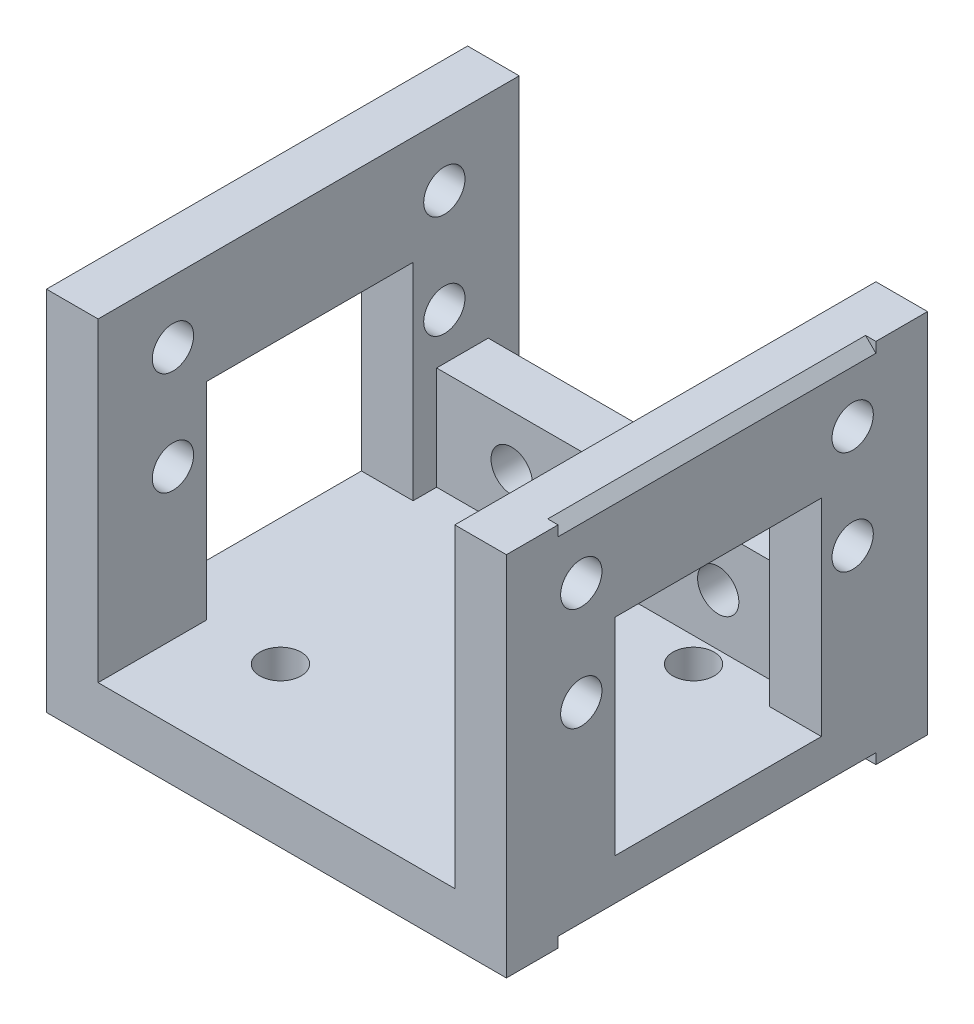
SolidWorks part; units mm, degrees
material "PEI"
ref_plane "前视基准面" through (0, 0, 0) normal (0, 0, 1) x (1, 0, 0)
ref_plane "上视基准面" through (0, 0, 0) normal (0, 1, 0) x (1, 0, 0)
ref_plane "右视基准面" through (0, 0, 0) normal (1, 0, 0) x (0, 0, -1)
other "Configuration Table"
sketch "草图1" plane through (0, 0, 0) normal (0, 0, 1) x (1, 0, 0)
  line L0 (0, 0) -> (58.1502, 0) construction
  line L5 (0, 0) -> (0, 35.5)
  line L6 (0, 0) -> (44.54, 0)
  line L7 (44.54, 0) -> (44.54, 35.5)
  line L8 (39.54, 5) -> (39.54, 35.5)
  line L9 (5, 5) -> (39.54, 5)
  line L10 (5, 5) -> (5, 35.5)
  line L11 (0, 35.5) -> (5, 35.5)
  line L12 (39.54, 35.5) -> (44.54, 35.5)
  dimension "D1" = 35.5
  dimension "D2" = 44.54
  dimension "D3" = 5
extrude "凸台-拉伸2" add sketch "草图1" along normal blind 34.78
sketch "草图2" plane through (44.54, 0, 0) normal (1, 0, 0) x (0, 0, -1)
  line L1 (-27.28, 5) -> (-7.28, 5)
  line L2 (-27.28, 5) -> (-27.28, 25)
  line L3 (-27.28, 25) -> (-7.28, 25)
  line L4 (-7.28, 5) -> (-7.28, 25)
  line L5 (-34.78, 0) -> (-34.78, 35.5) construction
  line L7 (-34.78, 0) -> (0, 0) construction
  dimension "D1" = 20
  dimension "D2" = 20
  dimension "D3" = 7.5
  dimension "D4" = 5
extrude "切除-拉伸1" cut sketch "草图2" against normal up to surface (44.54 mm away) up to face at (0, 17.75, 17.39)
chamfer "倒角1" distance 1 angle 45 9 edges at (44.54, 0, 17.39) (44.54, 17.75, 34.78) (44.54, 35.5, 17.39) (44.54, 17.75, 0) (0, 17.75, 0) (0, 17.75, 34.78) (22.27, 0, 0) (0, 0, 17.39) (22.27, 0, 34.78)
sketch "草图3" plane through (44.54, 0, 0) normal (1, 0, 0) x (0, 0, -1)
  line L0 (-33.78, 24.5) -> (-27.28, 24.5)
  line L1 (-33.78, 34.5) -> (-27.28, 34.5)
  line L2 (-33.78, 34.5) -> (-33.78, 5)
  line L3 (-33.78, 5) -> (-27.28, 5)
  line L4 (-27.28, 34.5) -> (-27.28, 5)
  line L5 (-33.78, 34.5) -> (-27.28, 24.5)
  line L6 (-27.28, 34.5) -> (-33.78, 24.5)
  line L7 (-1, 34.5) -> (-33.78, 34.5) construction
  line L8 (-1, 34.5) -> (-33.78, 34.5)
  line L9 (-17.39, 34.5) -> (-17.39, 26.7348) construction
  circle A0 centre (-30.53, 29.5) radius 2
  circle A1 centre (-4.25, 29.5) radius 2
  circle A2 centre (-4.25, 19.5) radius 2
  circle A3 centre (-30.53, 19.5) radius 2
  dimension "D2" = 4
  dimension "D1" = 10
extrude "切除-拉伸2" cut sketch "草图3" against normal up to surface (44.54 mm away) contours A3 | A2 | A1 | L5 A0 L6 | L6 A0 L5 | L5 A0 L6 | L6 A0 L5
sketch "草图4" plane through (0, 0, 0) normal (0, -1, 0) x (1, 0, 0)
  line L1 (12.27, 27.39) -> (32.27, 27.39) construction
  line L2 (12.27, 27.39) -> (12.27, 7.39) construction
  line L3 (12.27, 7.39) -> (32.27, 7.39) construction
  line L4 (1, 1) -> (43.54, 1)
  line L5 (43.54, 1) -> (43.54, 33.78)
  line L6 (43.54, 33.78) -> (1, 33.78)
  line L7 (1, 33.78) -> (1, 1)
  line L8 (1, 1) -> (43.54, 1)
  line L9 (43.54, 1) -> (43.54, 33.78)
  line L10 (43.54, 33.78) -> (1, 33.78)
  line L11 (1, 33.78) -> (1, 1)
  line L12 (32.27, 27.39) -> (32.27, 7.39) construction
  circle A0 centre (12.27, 27.39) radius 2
  circle A1 centre (12.27, 7.39) radius 2
  circle A2 centre (32.27, 7.39) radius 2
  circle A3 centre (32.27, 27.39) radius 2
  point P8 (22.27, 27.39)
  point P9 (22.27, 33.78)
  point P10 (12.27, 17.39)
  point P11 (1, 17.39)
  dimension "D4" = 4
  dimension "D5" = 4
  dimension "D6" = 4
  dimension "D7" = 4
  dimension "D2" = 20
  dimension "D3" = 20
  dimension "D1" = 0
extrude "切除-拉伸3" cut sketch "草图4" against normal up to surface (5 mm away) contours A1 | A0 | A3 | A2 up to face at (22.27, 5, 17.3167)
sketch "草图6" plane through (0, 5, 0) normal (0, 1, 0) x (1, 0, 0)
  line L1 (5, 0) -> (39.54, 0)
  line L2 (5, 0) -> (5, -5)
  line L3 (5, -5) -> (39.54, -5)
  line L4 (39.54, 0) -> (39.54, -5)
  line L5 (39.54, -34.78) -> (39.54, 0) construction
  dimension "D1" = 5
  dimension "D2" = 34.54
extrude "凸台-拉伸3" add sketch "草图6" along normal blind 10
sketch "草图8" plane through (0, 0, 5) normal (0, 0, 1) x (1, 0, 0)
  line L0 (5, 10) -> (39.54, 10) construction
  line L1 (22.27, 15) -> (22.27, 5) construction
  line L4 (5, 5) -> (39.54, 5)
  line L5 (39.54, 5) -> (39.54, 15)
  line L6 (39.54, 15) -> (5, 15)
  line L7 (5, 15) -> (5, 5)
  line L8 (5, 5) -> (39.54, 5)
  line L9 (39.54, 5) -> (39.54, 15)
  line L10 (39.54, 15) -> (5, 15)
  line L11 (5, 15) -> (5, 5)
  circle A0 centre (12.27, 10) radius 2
  circle A1 centre (32.27, 10) radius 2
  dimension "D2" = 4
  dimension "D3" = 4
  dimension "D4" = 10
  dimension "D5" = 10
  dimension "D1" = 0
extrude "切除-拉伸4" cut sketch "草图8" against normal up to surface (5 mm away) contours A0 | A1 up to face at (22.27, 21.75, 0)
ref_plane "基准面1" through (0, 0, 17.39) normal (0, 0, -1) x (-1, 0, 0)
sketch "草图9" plane through (0, 0, 34.78) normal (0, 0, 1) x (1, 0, 0)
  line L0 (44.54, 34.5) -> (44.54, 1) construction
  line L1 (0, 1) -> (0, 35.5) construction
  line L2 (43.54, 0) -> (1, 0) construction
  line L3 (5, 35.5) -> (1, 35.5) construction
  line L4 (39.54, 35.5) -> (39.54, 5) construction
  line L5 (39.54, 5) -> (5, 5) construction
  line L6 (5, 5) -> (5, 35.5) construction
  line L7 (44.54, 34.5) -> (44.54, 1)
  line L8 (0, 1) -> (0, 35.5)
  line L9 (43.54, 0) -> (1, 0)
  line L10 (5, 35.5) -> (1, 35.5)
  line L11 (39.54, 35.5) -> (39.54, 5)
  line L12 (39.54, 5) -> (5, 5)
  line L13 (5, 5) -> (5, 35.5)
  line L14 (1, 35.5) -> (0, 35.5)
  line L15 (39.54, 35.5) -> (44.54, 35.5)
  line L16 (44.54, 35.5) -> (44.54, 34.5)
  line L17 (44.54, 1) -> (44.54, 0)
  line L18 (44.54, 0) -> (43.54, 0)
  line L19 (1, 0) -> (0, 0)
  line L20 (0, 0) -> (0, 1)
extrude "凸台-拉伸4" add sketch "草图9" along normal blind 3 and the other way blind 2
mirror "镜向1" about plane through (0, 0, 17.39) normal (0, 0, -1) of "凸台-拉伸4"
equation "\"D2@草图1\"=\"髋_连接件长度\""
equation "\"髋距\"= 120"
equation "\"髋_连接件长度\"= \"髋距\" - 2 * \"安装距_髋关节\""
equation "\"安装距_髋关节\"= 37.73"
